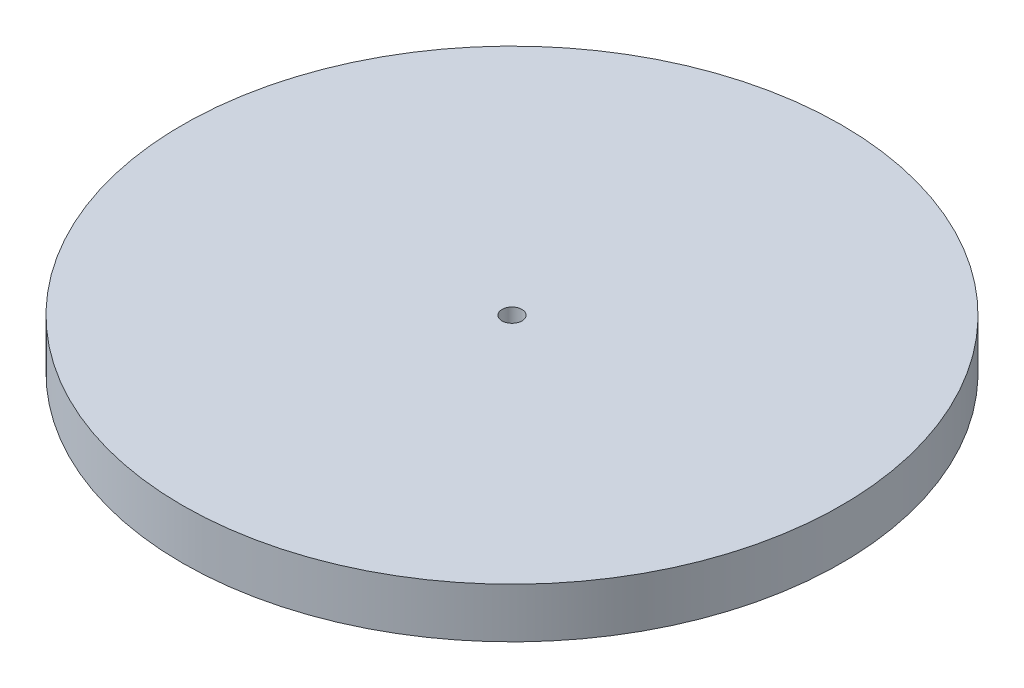
SolidWorks part; units mm, degrees
ref_plane "Front Plane" through (0, 0, 0) normal (0, 0, 1) x (1, 0, 0)
ref_plane "Top Plane" through (0, 0, 0) normal (0, 1, 0) x (1, 0, 0)
ref_plane "Right Plane" through (0, 0, 0) normal (1, 0, 0) x (0, 0, -1)
sketch "Sketch1" plane through (0, 0, 0) normal (0, 1, 0) x (1, 0, 0)
  circle A0 centre (0, 0) radius 66
  dimension "D1" = 132
extrude "Boss-Extrude1" add sketch "Sketch1" along normal blind 10
sketch "Sketch2" plane through (0, 10, 0) normal (0, 1, 0) x (1, 0, 0)
  circle A0 centre (0, 0) radius 2
  dimension "D1" = 4
extrude "Cut-Extrude1" cut sketch "Sketch2" against normal blind 10
